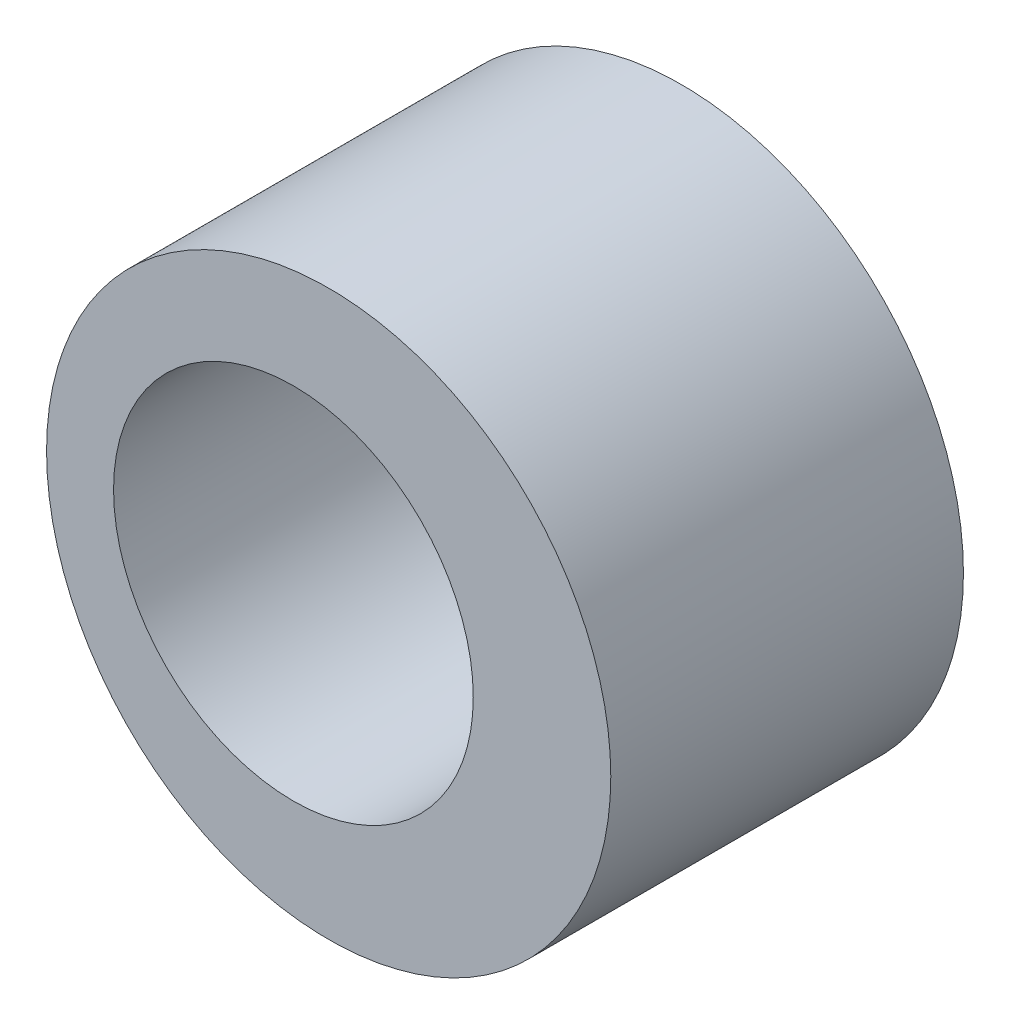
SolidWorks part; units mm, degrees
ref_plane "前视基准面" through (0, 0, 0) normal (0, 0, 1) x (1, 0, 0)
ref_plane "上视基准面" through (0, 0, 0) normal (0, 1, 0) x (1, 0, 0)
ref_plane "右视基准面" through (0, 0, 0) normal (1, 0, 0) x (0, 0, -1)
sketch "草图1" plane through (0, 0, 0) normal (0, 0, 1) x (1, 0, 0)
  circle A0 centre (0, 0) radius 4
  circle A2 centre (-0.5, 0) radius 2.55
extrude "凸台-拉伸1" add sketch "草图1" along normal blind 5
